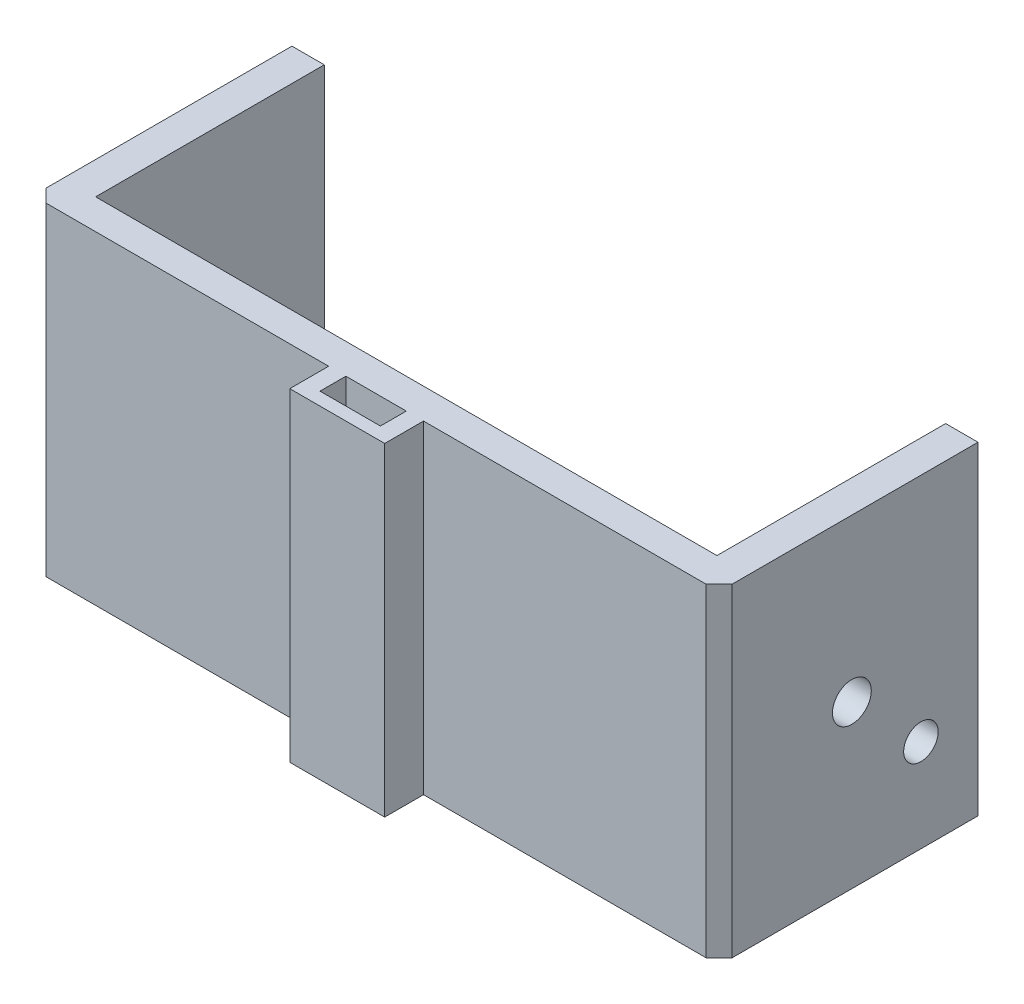
SolidWorks part; units mm, degrees
ref_plane "Front Plane" through (0, 0, 0) normal (0, 0, 1) x (1, 0, 0)
ref_plane "Top Plane" through (0, 0, 0) normal (0, 1, 0) x (1, 0, 0)
ref_plane "Right Plane" through (0, 0, 0) normal (1, 0, 0) x (0, 0, -1)
sketch "Sketch1" plane through (0, 0, 0) normal (0, 1, 0) x (1, 0, 0)
  line L0 (72, 0) -> (-72, 0)
  line L1 (-72, 0) -> (-72, 50)
  line L2 (-72, 50) -> (-79.5, 50)
  line L3 (-79.5, 50) -> (-79.5, -10)
  line L5 (79.5, -10) -> (11, -10)
  line L12 (0, 0) -> (0, -85.966) construction
  line L18 (79.5, 50) -> (79.5, -10)
  line L19 (72, 50) -> (79.5, 50)
  line L20 (72, 0) -> (72, 50)
  line L21 (7, -10) -> (7, -16)
  line L22 (7, -16) -> (-7, -16)
  line L23 (11, -10) -> (11, -19)
  line L24 (11, -19) -> (-11, -19)
  line L25 (7, -10) -> (-7, -10)
  line L26 (-11, -10) -> (-11, -19)
  line L27 (-7, -10) -> (-7, -16)
  line L28 (-11, -10) -> (-79.5, -10)
  point P15 (0, -19)
  point P16 (0, -16)
  point P25 (0, -55)
  point P26 (0, -10)
  point P27 (0, -62.5)
  point P30 (0, 0)
  dimension "D1" = 72
  dimension "D2" = 50
  dimension "D3" = 10
  dimension "D4" = 7.5
  dimension "D5" = 3
  dimension "D6" = 4
  dimension "D7" = 6
  dimension "D8" = 7
extrude "Boss-Extrude1" add sketch "Sketch1" along normal blind 75
sketch "Sketch2" plane through (0, 0, 0) normal (0, 0, -1) x (-1, 0, 0)
  line L0 (0, 75) -> (0, 0) construction
  line L1 (-72, 75) -> (72, 75) construction
  circle A0 centre (0, 37.5) radius 4.5
  dimension "D1" = 9
extrude "Cut-Extrude1" cut sketch "Sketch2" against normal up to surface (16 mm away) up to face at (0, 37.5, 16)
sketch "Sketch3" plane through (-72, 0, 0) normal (1, 0, 0) x (0, 0, -1)
  line L0 (0, 37.5) -> (20.77, 37.5) construction
  line L1 (0, 75) -> (0, 0) construction
  circle A0 centre (20.77, 37.5) radius 4.5
  dimension "D2" = 9
  dimension "D1" = 20.77
extrude "Cut-Extrude2" cut sketch "Sketch3" against normal through all both and the other way through all
chamfer "Chamfer1" distance 3 angle 45 3 edges at (0, 75, 0) (-79.5, 37.5, 10) (79.5, 37.5, 10)
sketch "Sketch4" plane through (79.5, 0, 0) normal (1, 0, 0) x (0, 0, -1)
  line L0 (-7, 75) -> (50, 75) construction
  line L1 (-7, 75) -> (-7, 0) construction
  circle A0 centre (36.77, 21.5) radius 4
  point P3 (0, 0)
  dimension "D1" = 8
  dimension "D2" = 43.77
  dimension "D3" = 53.5
extrude "Cut-Extrude3" cut sketch "Sketch4" against normal through all
